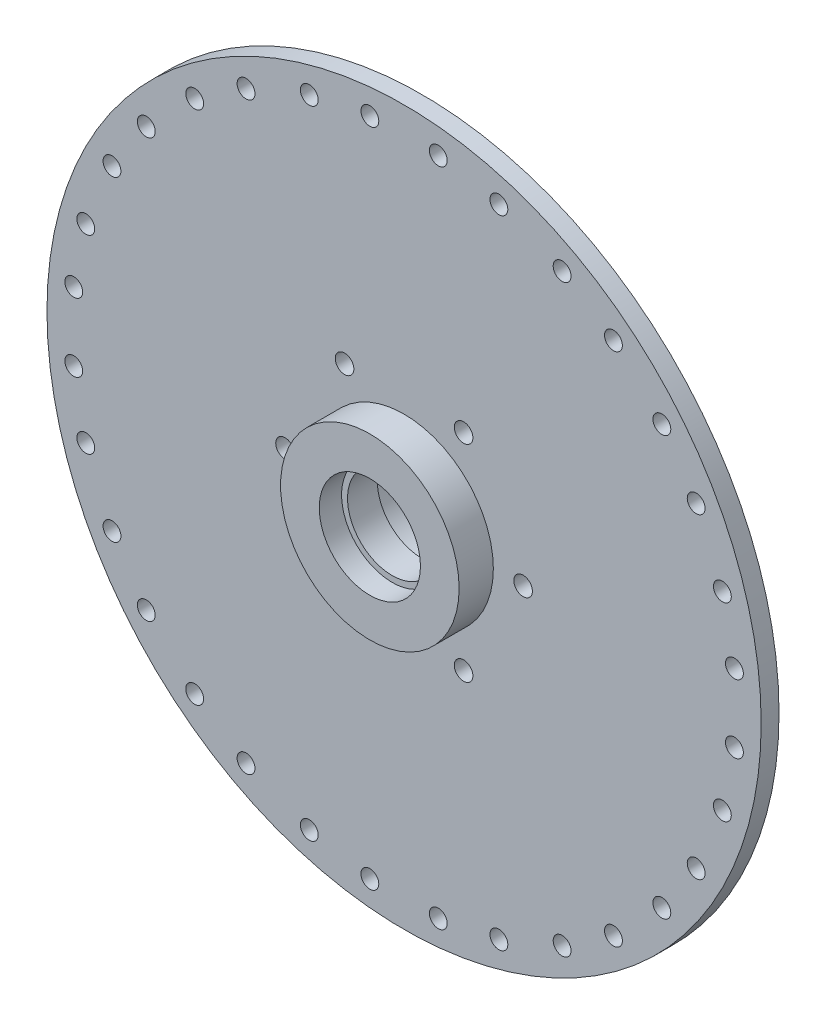
SolidWorks part; units mm, degrees
ref_plane "Piano frontale" through (0, 0, 0) normal (0, 0, 1) x (1, 0, 0)
ref_plane "Piano superiore" through (0, 0, 0) normal (0, 1, 0) x (1, 0, 0)
ref_plane "Piano destro" through (0, 0, 0) normal (1, 0, 0) x (0, 0, -1)
sketch "Schizzo1" plane through (0, 0, 0) normal (0, 0, 1) x (1, 0, 0)
  line L0 (0, 317.5795) -> (0, -73.3653) construction
  line L5 (-324.2951, 0) -> (324.2951, 0) construction
  line L17 (0, -324.2951) -> (0, 324.2951) construction
  circle A0 centre (0, 0) radius 240
  circle A41 centre (-80, 0) radius 6.25
  circle A42 centre (-40, 69.282) radius 6.25
  circle A43 centre (0, 0) radius 240
  circle A44 centre (40, 69.282) radius 6.25
  circle A45 centre (0, 0) radius 240
  circle A46 centre (80, 0) radius 6.25
  circle A47 centre (0, 0) radius 240
  circle A48 centre (40, -69.282) radius 6.25
  circle A49 centre (0, 0) radius 240
  circle A50 centre (-40, -69.282) radius 6.25
  circle A51 centre (0, 0) radius 240
  dimension "D3" = 6
  dimension "D2" = 80
  dimension "D1" = 12.5
extrude "Estrusione-Estrusione1" add sketch "Schizzo1" along normal blind 12 contours A0 A50 A48 A46 A44 A42 A41
sketch "Schizzo2" plane through (0, 0, 12) normal (0, 0, 1) x (1, 0, 0)
  circle A0 centre (0, 0) radius 60
  dimension "D1" = 120
extrude "Estrusione-Estrusione2" add sketch "Schizzo2" along normal blind 23 contours A0
sketch "Schizzo3" plane through (0, 0, 0) normal (0, 0, -1) x (-1, 0, 0)
  circle A0 centre (0, 0) radius 67.5
  dimension "D1" = 135
extrude "Estrusione-Estrusione3" add sketch "Schizzo3" along normal blind 15 contours A0
sketch "Schizzo4" plane through (0, 0, 35) normal (0, 0, 1) x (1, 0, 0)
  circle A0 centre (0, 0) radius 34
  dimension "D1" = 68
extrude "Taglio-Estrusione1" cut sketch "Schizzo4" against normal blind 15
sketch "Schizzo5" plane through (0, 0, 20) normal (0, 0, 1) x (1, 0, 0)
  circle A0 centre (0, 0) radius 30
  dimension "D1" = 60
extrude "Taglio-Estrusione2" cut sketch "Schizzo5" against normal blind 20 contours A0
sketch "Schizzo6" plane through (0, 0, -15) normal (0, 0, -1) x (-1, 0, 0)
  circle A0 centre (0, 0) radius 34
  dimension "D1" = 68
extrude "Taglio-Estrusione3" cut sketch "Schizzo6" against normal blind 15 contours A0
sketch "Schizzo7" plane through (0, 0, 12) normal (0, 0, 1) x (1, 0, 0)
  line L0 (0, 0) -> (-222, 0) construction
  line L1 (-222, 0) -> (-222, 23) construction
  line L2 (-222, 0) -> (-222, -23) construction
  circle A0 centre (-222, 23) radius 6
  circle A1 centre (-222, -23) radius 6
  dimension "D1" = 46
  dimension "D2" = 12
  dimension "D3" = 12
  dimension "D4" = 222
extrude "Taglio-Estrusione4" cut sketch "Schizzo7" against normal up to surface (12 mm away) up to face at (67.5, 0, 0)
pattern_circular "RipetizioneCircolare1" count 16 over 360 about axis through (0, 0, 0) along (0, 0, 1) of "Taglio-Estrusione4"
